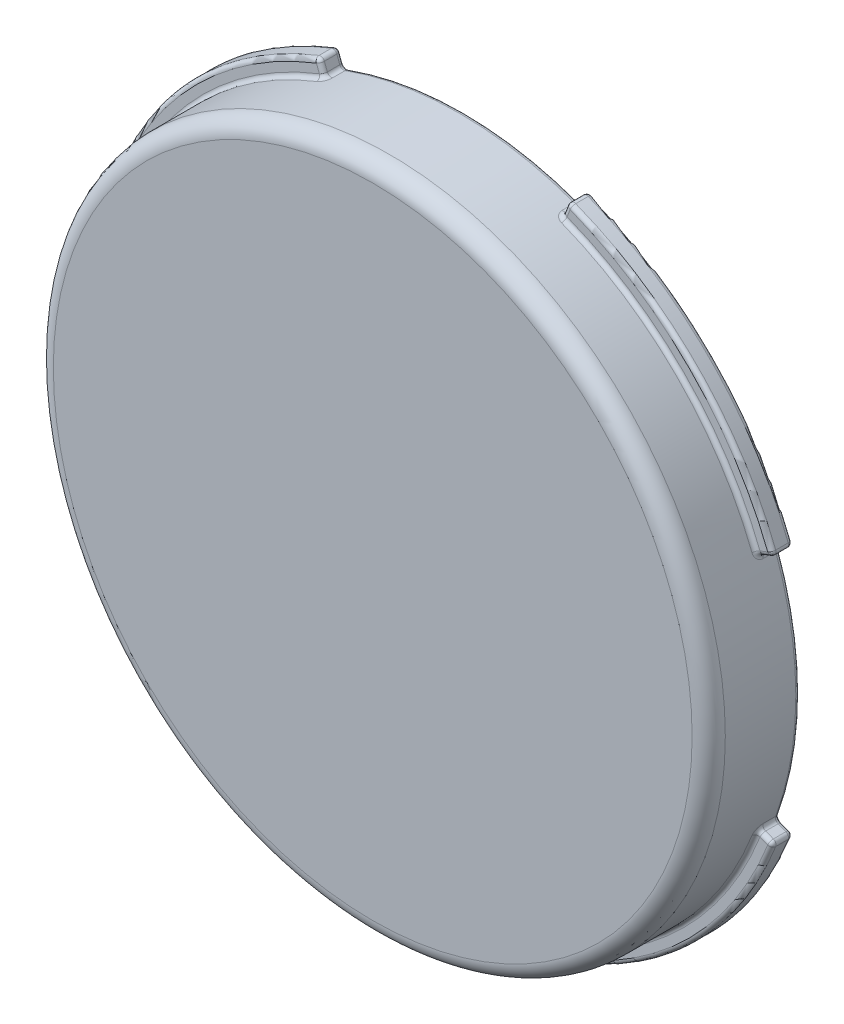
SolidWorks part; units mm, degrees
material "Glass"
ref_plane "Front Plane" through (0, 0, 0) normal (0, 0, 1) x (1, 0, 0)
ref_plane "Top Plane" through (0, 0, 0) normal (0, 1, 0) x (1, 0, 0)
ref_plane "Right Plane" through (0, 0, 0) normal (1, 0, 0) x (0, 0, -1)
sketch "Sketch1" plane through (0, 0, 0) normal (0, 0, 1) x (1, 0, 0)
  circle A0 centre (0, 0) radius 51.435
  dimension "D1" = 102.87
extrude "Boss-Extrude1" add sketch "Sketch1" along normal blind 13.97
fillet "Fillet1" radius 2.54 1 edges at (51.435, 0, 13.97)
shell "Shell1" thickness 2.8575
sketch "Sketch2" plane through (0, 0, 0) normal (0, 0, -1) x (-1, 0, 0)
  line L0 (-19.05, 50.5015) -> (-18.1535, 48.1249)
  line L1 (18.1535, 48.1249) -> (19.05, 50.5015)
  line L2 (0, 0) -> (0, 53.975) construction
  line L3 (48.1249, -18.1535) -> (50.5015, -19.05)
  line L4 (0, 0) -> (53.975, 0) construction
  line L5 (50.5015, 19.05) -> (48.1249, 18.1535)
  line L6 (-18.1535, -48.1249) -> (-19.05, -50.5015)
  line L7 (0, 0) -> (0, -53.975) construction
  line L8 (19.05, -50.5015) -> (18.1535, -48.1249)
  line L9 (-48.1249, 18.1535) -> (-50.5015, 19.05)
  line L10 (0, 0) -> (-53.975, 0) construction
  line L11 (-50.5015, -19.05) -> (-48.1249, -18.1535)
  arc A0 (-18.1535, 48.1249) -> (-48.1249, 18.1535) centre (0, 0) ccw
  arc A1 (-19.05, 50.5015) -> (-50.5015, 19.05) centre (0, 0) ccw
  arc A2 (50.5015, 19.05) -> (19.05, 50.5015) centre (0, 0) ccw
  arc A3 (48.1249, 18.1535) -> (18.1535, 48.1249) centre (0, 0) ccw
  arc A4 (19.05, -50.5015) -> (50.5015, -19.05) centre (0, 0) ccw
  arc A5 (18.1535, -48.1249) -> (48.1249, -18.1535) centre (0, 0) ccw
  arc A6 (-48.1249, -18.1535) -> (-18.1535, -48.1249) centre (0, 0) ccw
  arc A7 (-50.5015, -19.05) -> (-19.05, -50.5015) centre (0, 0) ccw
  point P19 (0, 0)
  dimension "D1" = 107.95
  dimension "D2" = 102.87
  dimension "D3" = 38.1
  dimension "D4" = 4
extrude "Boss-Extrude2" add sketch "Sketch2" against normal blind 3.175
fillet "Fillet2" radius 0.635 49 edges at (-18.1535, -48.1249, 1.5875) (-48.1249, -18.1535, 1.5875) (18.1535, -48.1249, 1.5875) (48.1249, -18.1535, 1.5875) (-48.1249, 18.1535, 1.5875) (-18.1535, 48.1249, 1.5875) (48.1249, 18.1535, 1.5875) (18.1535, 48.1249, 1.5875) (50.5015, 19.05, 1.5875) (19.05, 50.5015, 1.5875) (-50.5015, -19.05, 1.5875) (-19.05, -50.5015, 1.5875) (-18.6018, -49.3132, 3.175) (-38.1661, -38.1661, 3.175) (-49.3132, -18.6018, 3.175) (-36.37, -36.37, 3.175) (18.6018, -49.3132, 3.175) (36.37, -36.37, 3.175) (49.3132, -18.6018, 3.175) (19.05, -50.5015, 1.5875) (38.1661, -38.1661, 3.175) (50.5015, -19.05, 1.5875) (-49.3132, -18.6018, 0) (-38.1661, -38.1661, 0) (-18.6018, -49.3132, 0) (0, -51.435, 0) (18.6018, -49.3132, 0) (38.1661, -38.1661, 0) (49.3132, -18.6018, 0) (51.435, 0, 0) (49.3132, 18.6018, 0) (49.3132, 18.6018, 3.175) (38.1661, 38.1661, 0) (38.1661, 38.1661, 3.175) (18.6018, 49.3132, 0) (18.6018, 49.3132, 3.175) (0, 51.435, 0) (-18.6018, 49.3132, 0) (-18.6018, 49.3132, 3.175) (-49.3132, 18.6018, 0) (-49.3132, 18.6018, 3.175) (-51.435, 0, 0) (48.5775, 0, 0) (-19.05, 50.5015, 1.5875) (-50.5015, 19.05, 1.5875) (-38.1661, 38.1661, 0) (-38.1661, 38.1661, 3.175) (-36.37, 36.37, 3.175) (36.37, 36.37, 3.175)
